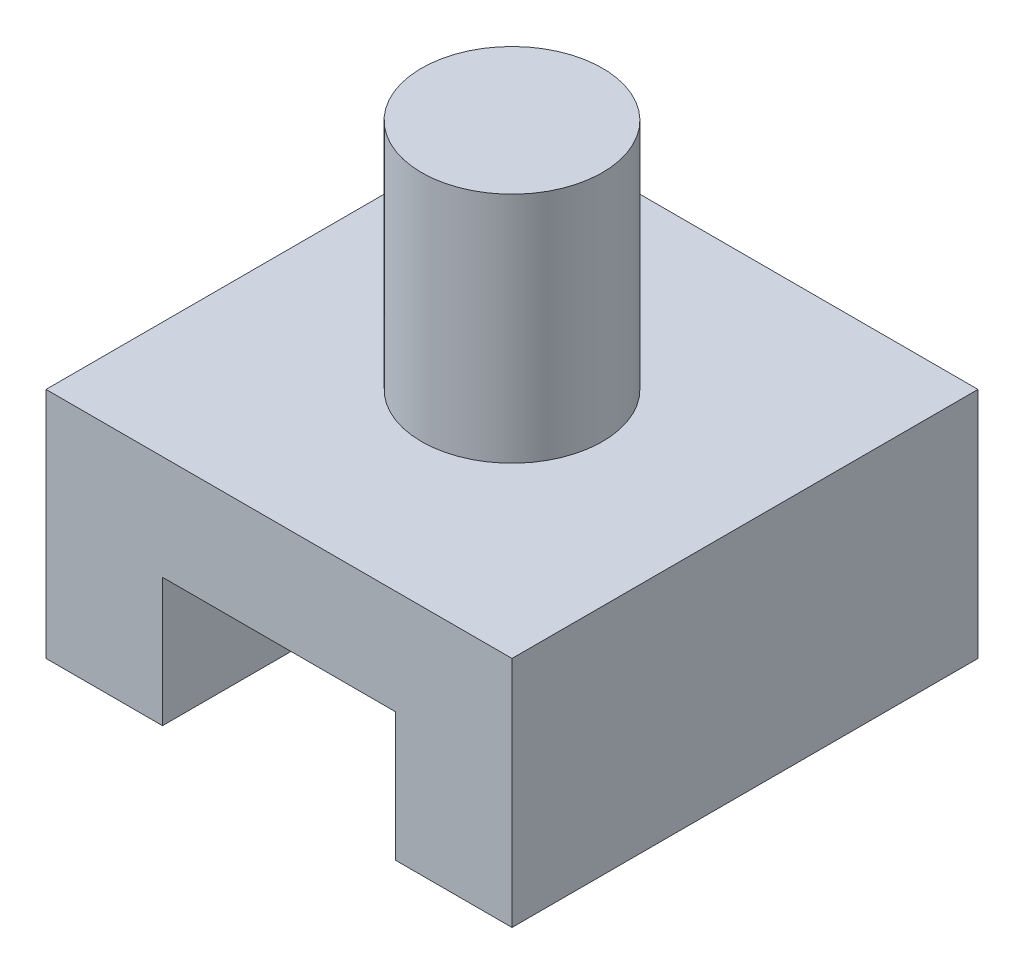
SolidWorks part; units mm, degrees
ref_plane "Front Plane" through (0, 0, 0) normal (0, 0, 1) x (1, 0, 0)
ref_plane "Top Plane" through (0, 0, 0) normal (0, 1, 0) x (1, 0, 0)
ref_plane "Right Plane" through (0, 0, 0) normal (1, 0, 0) x (0, 0, -1)
sketch "Sketch1" plane through (0, 0, 0) normal (0, 1, 0) x (1, 0, 0)
  line L0 (0, 0) -> (-40, 0)
  line L1 (-40, 0) -> (-40, 40)
  line L2 (-40, 40) -> (0, 40)
  line L3 (0, 40) -> (0, 0)
  dimension "D1" = 40
  dimension "D2" = 40
extrude "Boss-Extrude1" add sketch "Sketch1" along normal blind 20
sketch "Sketch2" plane through (0, 0, 0) normal (0, 0, 1) x (1, 0, 0)
  line L0 (-30, 0) -> (-30, 11.0354)
  line L1 (-40, 0) -> (0, 0) construction
  line L2 (-30, 11.0354) -> (-10, 11.0354)
  line L3 (-10, 11.0354) -> (-10, 0)
  line L4 (-10, 0) -> (-30, 0)
  dimension "D1" = 10
  dimension "D2" = 10
extrude "Cut-Extrude1" cut sketch "Sketch2" against normal through all
sketch "Sketch3" plane through (0, 20, 0) normal (0, 1, 0) x (1, 0, 0)
  circle A0 centre (-20, 20) radius 7.7653
extrude "Boss-Extrude2" add sketch "Sketch3" along normal blind 20
